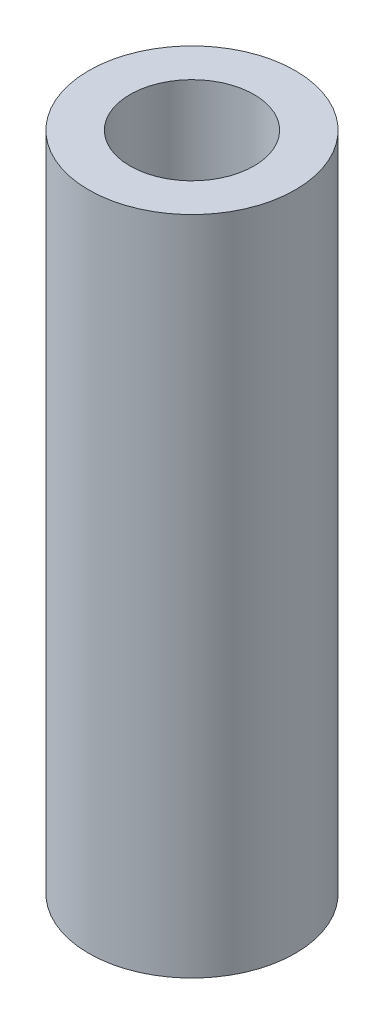
SolidWorks part; units mm, degrees
ref_plane "前视基准面" through (0, 0, 0) normal (0, 0, 1) x (1, 0, 0)
ref_plane "上视基准面" through (0, 0, 0) normal (0, 1, 0) x (1, 0, 0)
ref_plane "右视基准面" through (0, 0, 0) normal (1, 0, 0) x (0, 0, -1)
sketch "草图1" plane through (0, 0, 0) normal (0, 1, 0) x (1, 0, 0)
  circle A0 centre (0, 0) radius 2.5
  circle A1 centre (0, 0) radius 1.5
  dimension "D1" = 3
  dimension "D2" = 5
extrude "凸台-拉伸1" add sketch "草图1" along normal blind 16
